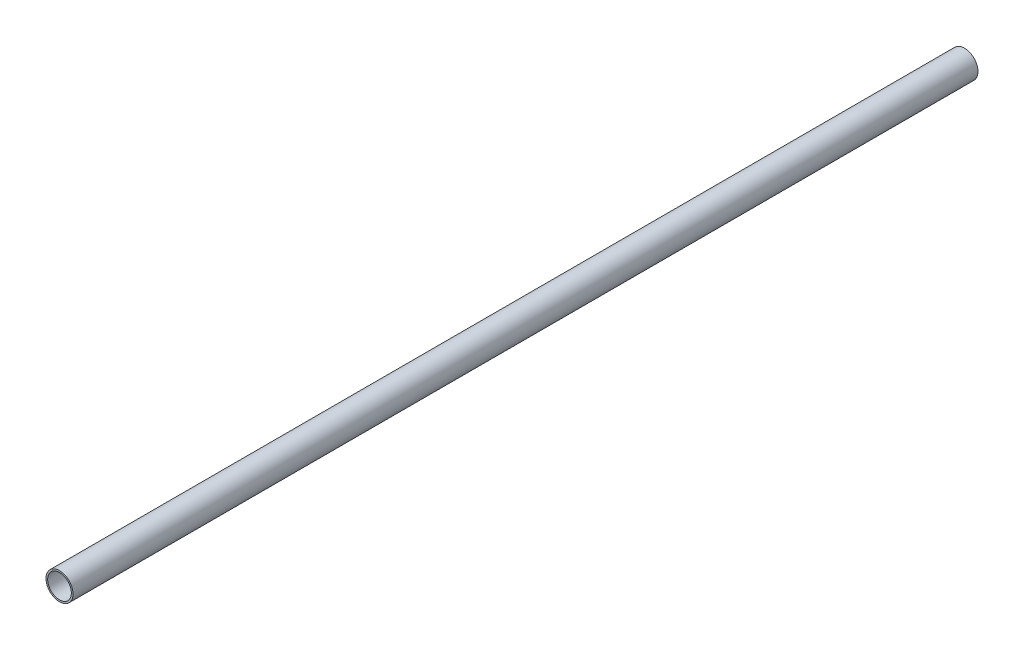
SolidWorks part; units mm, degrees
material "Poltrusion Carbon Fiber"
ref_plane "Front Plane" through (0, 0, 0) normal (0, 0, 1) x (1, 0, 0)
ref_plane "Top Plane" through (0, 0, 0) normal (0, 1, 0) x (1, 0, 0)
ref_plane "Right Plane" through (0, 0, 0) normal (1, 0, 0) x (0, 0, -1)
sketch "Эскиз1" plane through (0, 0, 0) normal (0, 0, 1) x (1, 0, 0)
  circle A0 centre (0, 0) radius 8
  circle A1 centre (0, 0) radius 7
  dimension "D1" = 16
  dimension "D2" = 1
extrude "Бобышка-Вытянуть1" add sketch "Эскиз1" along normal blind 535 contours A0
